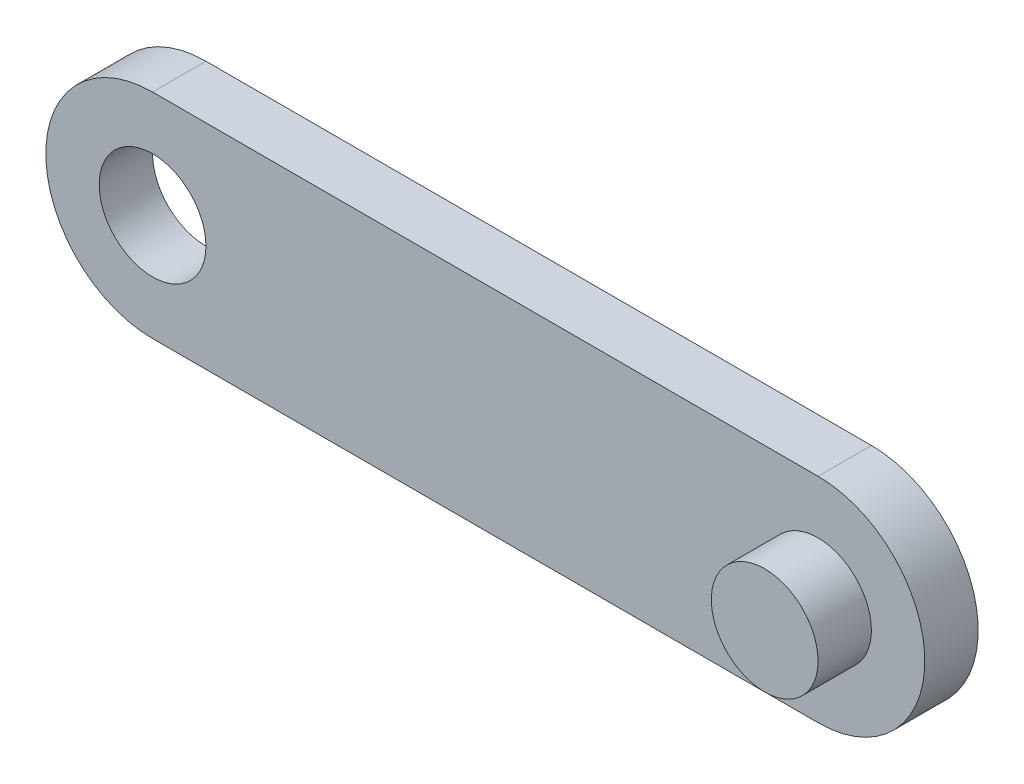
SolidWorks part; units mm, degrees
ref_plane "정면" through (0, 0, 0) normal (0, 0, 1) x (1, 0, 0)
ref_plane "윗면" through (0, 0, 0) normal (0, 1, 0) x (1, 0, 0)
ref_plane "우측면" through (0, 0, 0) normal (1, 0, 0) x (0, 0, -1)
sketch "스케치1" plane through (0, 0, 0) normal (0, 0, 1) x (1, 0, 0)
  line L1 (0, 20) -> (124.6809, 20)
  line L3 (0, -20) -> (124.6809, -20)
  arc A0 (0, 20) -> (0, -20) centre (0, 0) ccw
  arc A1 (124.6809, -20) -> (124.6809, 20) centre (124.6809, 0) ccw
  circle A2 centre (0, 0) radius 10
extrude "보스-돌출1" add sketch "스케치1" along normal blind 10
sketch "스케치2" plane through (0, 0, 10) normal (0, 0, 1) x (1, 0, 0)
  circle A0 centre (124.6809, 0) radius 10
extrude "보스-돌출2" add sketch "스케치2" along normal blind 10
